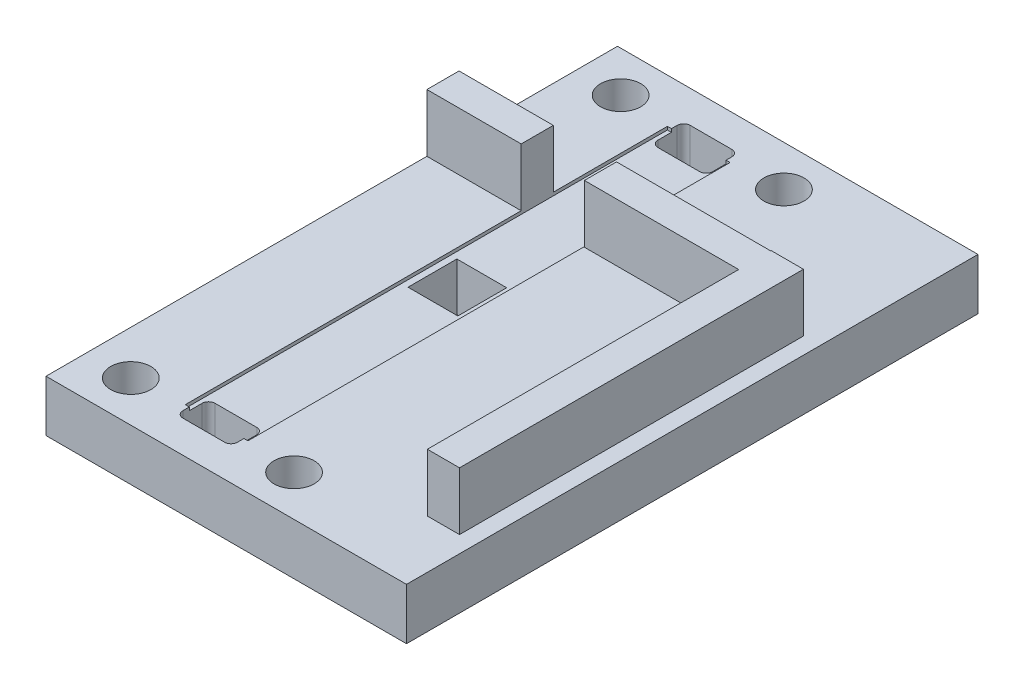
SolidWorks part; units mm, degrees
ref_plane "Front Plane" through (0, 0, 0) normal (0, 0, 1) x (1, 0, 0)
ref_plane "Top Plane" through (0, 0, 0) normal (0, 1, 0) x (1, 0, 0)
ref_plane "Right Plane" through (0, 0, 0) normal (1, 0, 0) x (0, 0, -1)
sketch "Sketch1" plane through (0, 0, 0) normal (0, 1, 0) x (1, 0, 0)
  line L1 (-96.4286, 88.9) -> (96.4286, 88.9)
  line L2 (-96.4286, 88.9) -> (-96.4286, -88.9)
  line L3 (-96.4286, -88.9) -> (96.4286, -88.9)
  line L4 (96.4286, 88.9) -> (96.4286, -88.9)
  line L5 (-96.4286, 88.9) -> (96.4286, -88.9) construction
  line L6 (-96.4286, -88.9) -> (96.4286, 88.9) construction
  point P0 (0, 0)
  dimension "D1" = 177.8
extrude "Boss-Extrude1" add sketch "Sketch1" along normal blind 16
sketch "Sketch2" plane through (0, 16, 0) normal (0, 1, 0) x (1, 0, 0)
  line L2 (-96.4286, 88.9) -> (96.4286, 88.9) construction
  line L3 (-25.4, 88.9) -> (-25.4, -76.2)
  line L5 (25.4, 88.9) -> (25.4, -76.2)
  line L8 (25.4, 88.9) -> (25.4, 76.2)
  line L9 (-25.4, 88.9) -> (-25.4, 76.2)
sketch "Sketch3" plane through (0, 16, 0) normal (0, 1, 0) x (1, 0, 0)
  circle A0 centre (-25.4, 76.2) radius 6.25
  circle A1 centre (25.4, 76.2) radius 6.25
  circle A2 centre (25.4, -76.2) radius 6.25
  circle A3 centre (-25.4, -76.2) radius 6.25
extrude "Cut-Extrude1" cut sketch "Sketch3" against normal blind 12.7
sketch "Sketch6" plane through (0, 0, 0) normal (0, -1, 0) x (-1, 0, 0)
  circle A0 centre (25.4, -76.2) radius 3.5
  circle A1 centre (-25.4, -76.2) radius 3.5
  circle A2 centre (-25.4, 76.2) radius 3.5
  circle A3 centre (25.4, 76.2) radius 3.5
extrude "Cut-Extrude2" cut sketch "Sketch6" against normal through all both and the other way through all
sketch "Sketch7" plane through (0, 16, 0) normal (0, 1, 0) x (1, 0, 0)
  line L0 (-25.4, 88.9) -> (-25.4, -76.2) construction
  line L1 (-7.75, -7.6) -> (7.75, -7.6)
  line L2 (-7.75, -7.6) -> (-7.75, 7.6)
  line L3 (-7.75, 7.6) -> (7.75, 7.6)
  line L4 (7.75, -7.6) -> (7.75, 7.6)
  line L5 (-7.75, -7.6) -> (7.75, 7.6) construction
  line L6 (-7.75, 7.6) -> (7.75, -7.6) construction
  point P0 (0, 0)
  dimension "D1" = 15.2
  dimension "D3" = 17.65
extrude "Cut-Extrude3" cut sketch "Sketch7" against normal through all both and the other way through all
ref_plane "Plane1" through (0, 0, 0) normal (0, 0, 1) x (1, 0, 0)
ref_plane "Plane2" through (-96.4286, 0, -88.9) normal (1, 0, 0) x (0, 0, -1)
sketch "Sketch17" plane through (0, 16, 0) normal (0, 1, 0) x (1, 0, 0)
  line L0 (96.4286, -88.9) -> (-96.4286, -88.9) construction
  line L1 (96.4286, 88.9) -> (38.0786, 88.9)
  line L2 (96.4286, 88.9) -> (96.4286, -88.9)
  line L3 (96.4286, -88.9) -> (38.0786, -88.9)
  line L4 (38.0786, 88.9) -> (38.0786, -88.9)
  dimension "D1" = 58.35
extrude "Cut-Extrude10" cut sketch "Sketch17" against normal through all both and the other way through all
ref_plane "Plane3" through (-0.5, 0, 0) normal (1, 0, 0) x (0, 0, -1)
mirror "Mirror5" about plane through (-0.5, 0, 0) normal (1, 0, 0) of "Cut-Extrude10"
sketch "Sketch18" plane through (0, 16, 0) normal (0, 1, 0) x (1, 0, 0)
  line L0 (-25.4, 88.9) -> (-25.4, -76.2) construction
  line L1 (8.5, -78.9) -> (-8.5, -78.9)
  line L2 (8.5, -78.9) -> (8.5, -68.9)
  line L3 (8.5, -68.9) -> (-8.5, -68.9)
  line L4 (-8.5, -78.9) -> (-8.5, -68.9)
  line L5 (8.5, -78.9) -> (-8.5, -68.9) construction
  line L6 (8.5, -68.9) -> (-8.5, -78.9) construction
  line L7 (-39.0786, -88.9) -> (38.0786, -88.9) construction
  point P0 (0, -73.9)
  dimension "D1" = 17
  dimension "D2" = 10
  dimension "D3" = 10
extrude "Cut-Extrude11" cut sketch "Sketch18" against normal through all
fillet "Fillet1" radius 2 4 edges at (-8.5, 8, 78.9) (8.5, 8, 78.9) (8.5, 8, 68.9) (-8.5, 8, 68.9)
sketch "Sketch19" plane through (0, 16, 0) normal (0, 1, 0) x (1, 0, 0)
  line L0 (7.75, 7.6) -> (-7.75, 7.6) construction
  line L1 (57.9214, 39.6) -> (9.9214, 39.6)
  line L2 (57.9214, 39.6) -> (57.9214, 29.6)
  line L3 (57.9214, 29.6) -> (9.9214, 29.6)
  line L4 (9.9214, 39.6) -> (9.9214, 29.6)
  line L5 (57.9214, 39.6) -> (9.9214, 29.6) construction
  line L6 (57.9214, 29.6) -> (9.9214, 39.6) construction
  line L7 (-39.0786, 88.9) -> (-39.0786, -88.9) construction
  point P9 (57.9214, 34.6)
  point P10 (9.9214, 34.6)
  dimension "D1" = 22
  dimension "D2" = 48
  dimension "D3" = 10
  dimension "D5" = 49
extrude "Boss-Extrude2" add sketch "Sketch19" along normal blind 18
sketch "Sketch20" plane through (38.0786, 0, 0) normal (1, 0, 0) x (0, 0, -1)
  line L1 (-88.9, 0) -> (88.9, 0)
  line L2 (-88.9, 0) -> (-88.9, 16)
  line L3 (-88.9, 16) -> (88.9, 16)
  line L4 (88.9, 0) -> (88.9, 16)
extrude "Boss-Extrude3" add sketch "Sketch20" along normal blind 35
sketch "Sketch21" plane through (0, 16, 0) normal (0, 1, 0) x (1, 0, 0)
  line L1 (57.9214, 39.75) -> (67.9214, 39.75)
  line L2 (57.9214, 39.75) -> (57.9214, -67.25)
  line L3 (57.9214, -67.25) -> (67.9214, -67.25)
  line L4 (67.9214, 39.75) -> (67.9214, -67.25)
  line L5 (73.0786, 88.9) -> (-39.0786, 88.9) construction
  line L6 (-39.0786, 88.9) -> (-39.0786, -88.9) construction
  point P6 (62.9214, 39.75)
  dimension "D1" = 97
  dimension "D2" = 10
  dimension "D3" = 107
  dimension "D4" = 49.15
extrude "Boss-Extrude4" add sketch "Sketch21" along normal blind 18
sketch "Sketch22" plane through (0, 16, 0) normal (0, 1, 0) x (1, 0, 0)
  line L1 (9.75, -74.9038) -> (-9.75, -74.9038)
  line L2 (9.75, -74.9038) -> (9.75, 75.0962)
  line L3 (9.75, 75.0962) -> (-9.75, 75.0962)
  line L4 (-9.75, -74.9038) -> (-9.75, 75.0962)
  point P0 (0, 0)
  dimension "D1" = 19.5
  dimension "D2" = 150
sketch "Sketch23" plane through (0, 16, 0) normal (0, 1, 0) x (1, 0, 0)
  line L0 (73.0786, 88.9) -> (-39.0786, 88.9) construction
  line L1 (8.5, 68.9) -> (-8.5, 68.9)
  line L2 (8.5, 68.9) -> (8.5, 78.9)
  line L3 (8.5, 78.9) -> (-8.5, 78.9)
  line L4 (-8.5, 68.9) -> (-8.5, 78.9)
  line L5 (8.5, 68.9) -> (-8.5, 78.9) construction
  line L6 (8.5, 78.9) -> (-8.5, 68.9) construction
  point P0 (0, 73.9)
  dimension "D1" = 10
  dimension "D2" = 10
  dimension "D3" = 17
extrude "Cut-Extrude12" cut sketch "Sketch23" against normal blind 30
fillet "Fillet2" radius 2 4 edges at (8.5, 8, -68.9) (-8.5, 8, -68.9) (-8.5, 8, -78.9) (8.5, 8, -78.9)
extrude "Cut-Extrude13" cut sketch "Sketch22" against normal blind 1
sketch "Sketch24" plane through (0, 16, 0) normal (0, 1, 0) x (1, 0, 0)
  line L0 (-9.75, 75.0962) -> (-9.75, -74.9038) construction
  line L1 (-9.75, 39.6) -> (-39.0786, 39.6)
  line L2 (-9.75, 39.6) -> (-9.75, 29.6)
  line L3 (-9.75, 29.6) -> (-39.0786, 29.6)
  line L4 (-39.0786, 39.6) -> (-39.0786, 29.6)
  line L5 (-39.0786, 88.9) -> (-39.0786, -88.9) construction
  line L6 (9.9214, 29.6) -> (57.9214, 29.6) construction
  dimension "D1" = 10
  dimension "D2" = 0
extrude "Boss-Extrude5" add sketch "Sketch24" along normal blind 18
